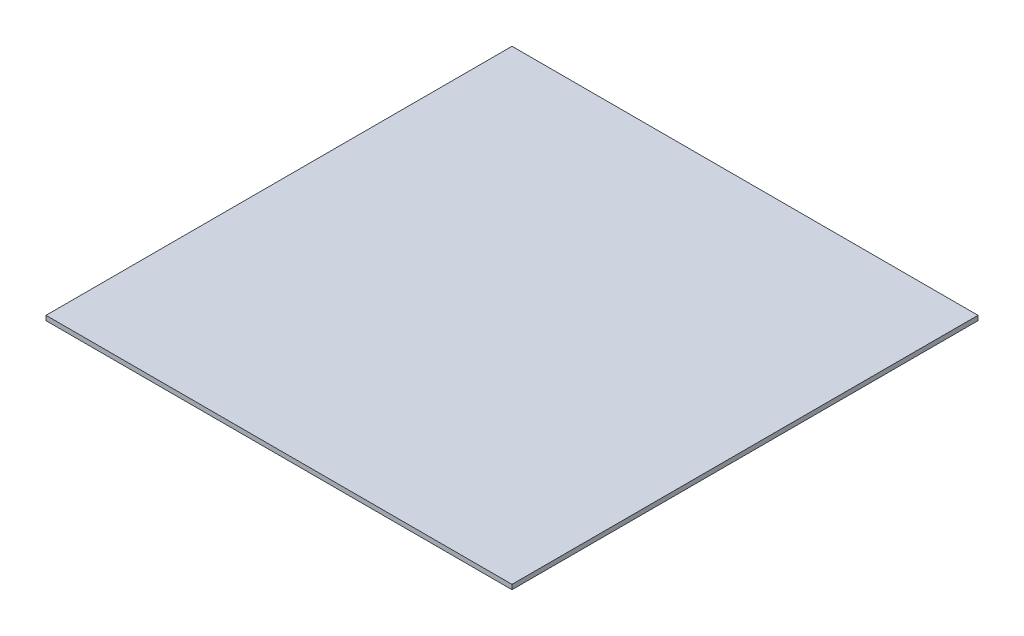
SolidWorks part; units mm, degrees
ref_plane "Front Plane" through (0, 0, 0) normal (0, 0, 1) x (1, 0, 0)
ref_plane "Top Plane" through (0, 0, 0) normal (0, 1, 0) x (1, 0, 0)
ref_plane "Right Plane" through (0, 0, 0) normal (1, 0, 0) x (0, 0, -1)
sketch "Sketch1" plane through (0, 0, 0) normal (0, 1, 0) x (1, 0, 0)
  line L1 (-100, 100) -> (100, 100)
  line L2 (-100, 100) -> (-100, -100)
  line L3 (-100, -100) -> (100, -100)
  line L4 (100, 100) -> (100, -100)
  line L5 (-100, 100) -> (100, -100) construction
  line L6 (-100, -100) -> (100, 100) construction
  point P0 (0, 0)
  dimension "D1" = 200
extrude "Boss-Extrude1" add sketch "Sketch1" along normal blind 2
